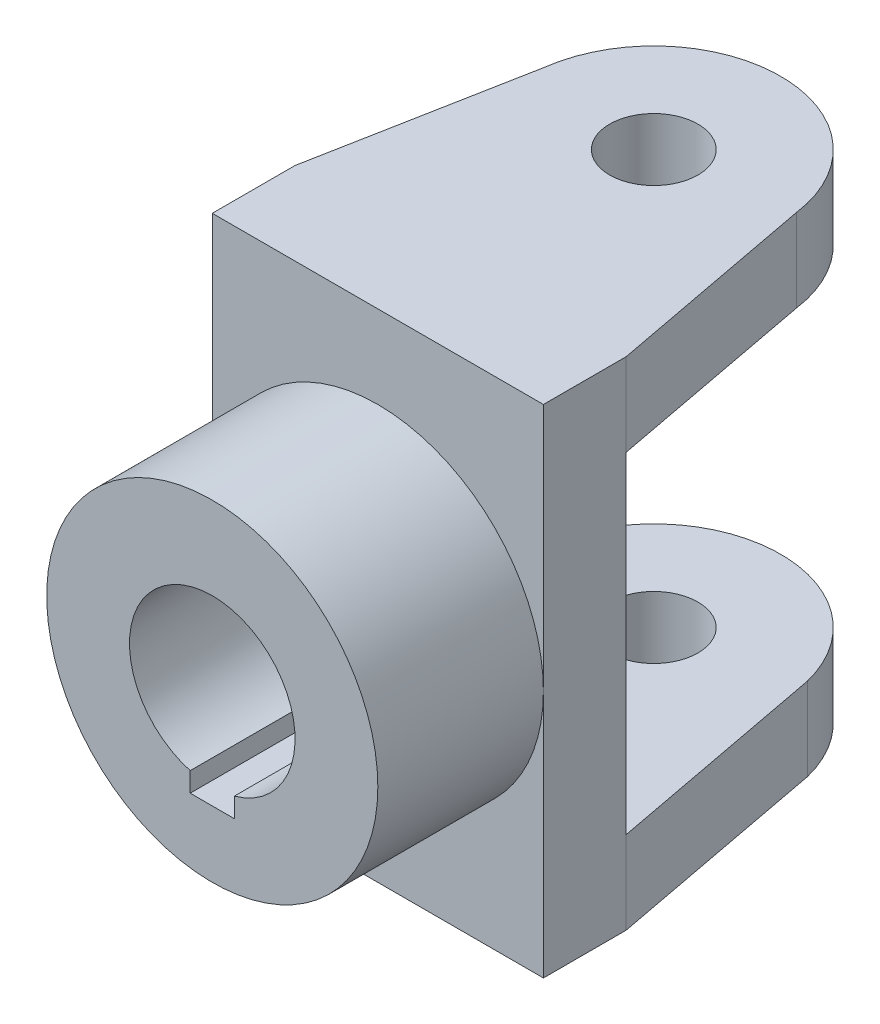
SolidWorks part; units mm, degrees
ref_plane "Front Plane" through (0, 0, 0) normal (0, 0, 1) x (1, 0, 0)
ref_plane "Top Plane" through (0, 0, 0) normal (0, 1, 0) x (1, 0, 0)
ref_plane "Right Plane" through (0, 0, 0) normal (1, 0, 0) x (0, 0, -1)
sketch "Sketch1" plane through (0, 0, 0) normal (0, 0, 1) x (1, 0, 0)
  line L1 (-30, 45) -> (30, 45)
  line L2 (-30, 45) -> (-30, -45)
  line L3 (-30, -45) -> (30, -45)
  line L4 (30, 45) -> (30, -45)
  point P0 (0, 0)
  dimension "D1" = 60
  dimension "D2" = 30
  dimension "D3" = 90
  dimension "D4" = 45
extrude "Boss-Extrude1" add sketch "Sketch1" along normal blind 15
sketch "Sketch2" plane through (0, 0, 15) normal (0, 0, 1) x (1, 0, 0)
  circle A0 centre (0, 0) radius 15
  circle A1 centre (0, 0) radius 30
  dimension "D1" = 60
  dimension "D2" = 30
extrude "Boss-Extrude2" add sketch "Sketch2" along normal blind 30
sketch "Sketch3" plane through (0, 0, 45) normal (0, 0, 1) x (1, 0, 0)
  line L1 (-4, -18) -> (4, -18)
  line L3 (-4, -14.4568) -> (-4, -18)
  line L4 (4, -14.4568) -> (4, -18)
  arc A0 (4, -14.4568) -> (-4, -14.4568) centre (0, 0) ccw
  circle A1 centre (0, 0) radius 30 construction
  point P5 (-45.435, -18)
  point P6 (42.1717, -18)
  point P8 (-4, 0)
  point P10 (4, 0)
  dimension "D1" = 15
  dimension "D2" = 8
  dimension "D3" = 18
extrude "Cut-Extrude1" cut sketch "Sketch3" against normal blind 30
sketch "Sketch4" plane through (0, 45, 0) normal (0, 1, 0) x (1, 0, 0)
  line L0 (-30, -15) -> (-30, 0) construction
  line L1 (-30, 0) -> (-22.7945, 38.0676)
  line L2 (30, 0) -> (22.7945, 38.0676)
  line L3 (-30, 0) -> (30, 0)
  line L4 (30, 0) -> (-30, 0) construction
  circle A0 centre (0, 35) radius 8
  arc A1 (22.7945, 38.0676) -> (-22.7945, 38.0676) centre (0, 35) ccw
  dimension "D2" = 46
  dimension "D3" = 16
  dimension "D1" = 7.2055
  dimension "D4" = 30
  dimension "D5" = 35
  dimension "D6" = 60
extrude "Boss-Extrude4" add sketch "Sketch4" against normal blind 15 contours A1 L1 L3 L2 | A0
sketch "Sketch8" plane through (0, -45, 0) normal (0, -1, 0) x (1, 0, 0)
  line L0 (-30, 0) -> (-22.3269, -40.5235)
  line L1 (30, 0) -> (22.3269, -40.5235)
  line L2 (-30, 0) -> (30, 0)
  circle A0 centre (0, -35) radius 8
  arc A1 (-22.8007, -38.0214) -> (22.8007, -38.0214) centre (0, -35) ccw
  line M2 (-30, 0) -> (30, 0)
extrude "Boss-Extrude5" add sketch "Sketch8" against normal blind 15 contours L0 A1 L1 A0 M2
